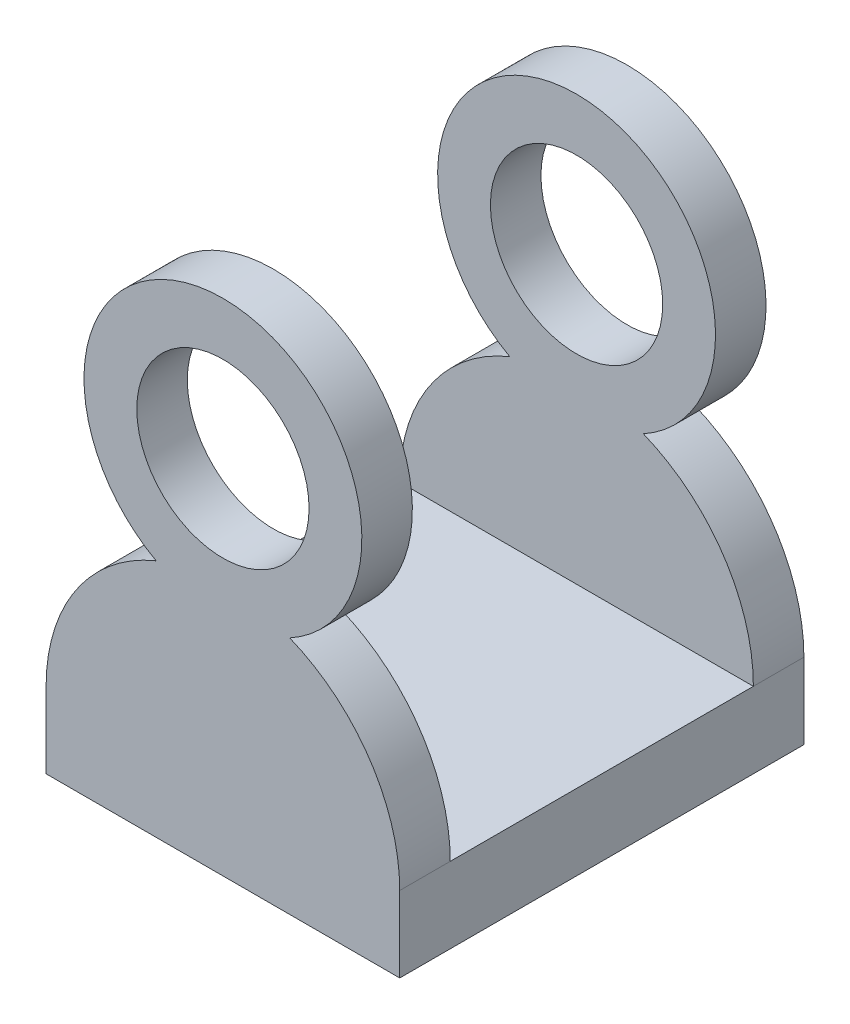
SolidWorks part; units mm, degrees
ref_plane "Front Plane" through (0, 0, 0) normal (0, 0, 1) x (1, 0, 0)
ref_plane "Top Plane" through (0, 0, 0) normal (0, 1, 0) x (1, 0, 0)
ref_plane "Right Plane" through (0, 0, 0) normal (1, 0, 0) x (0, 0, -1)
sketch "Sketch1" plane through (0, 0, 0) normal (0, 0, 1) x (1, 0, 0)
  line L1 (-7, -1.5) -> (7, -1.5)
  line L2 (-7, -1.5) -> (-7, 1.5)
  line L3 (-7, 1.5) -> (7, 1.5)
  line L4 (7, -1.5) -> (7, 1.5)
  line L5 (-7, -1.5) -> (7, 1.5) construction
  line L6 (-7, 1.5) -> (7, -1.5) construction
  point P0 (0, 0)
  dimension "D1" = 3
  dimension "D2" = 14
extrude "Boss-Extrude1" add sketch "Sketch1" along normal blind 16
sketch "Sketch2" plane through (0, 0, 16) normal (0, 0, 1) x (1, 0, 0)
  line L1 (7, 1.5) -> (-7, 1.5) construction
  line L2 (-7, 1.5) -> (7, 1.5)
  arc A0 (7, 1.5) -> (2.6439, 7.9815) centre (0, 1.5) ccw
  arc A1 (2.6439, 7.9815) -> (-2.6439, 7.9815) centre (0, 12.8043) ccw
  arc A2 (-2.6439, 7.9815) -> (-7, 1.5) centre (0, 1.5) ccw
  dimension "D1" = 5.5
extrude "Boss-Extrude2" add sketch "Sketch2" against normal blind 2
sketch "Sketch3" plane through (0, 0, 16) normal (0, 0, 1) x (1, 0, 0)
  line L0 (-7, -1.5) -> (7, -1.5) construction
  circle A0 centre (0, 12.8043) radius 3.41
  point P5 (0, -1.5)
  dimension "D2" = 6.82
extrude "Cut-Extrude2" cut sketch "Sketch3" against normal blind 7.8
ref_plane "Plane2" through (0, 0, 8) normal (0, 0, -1) x (-1, 0, 0)
mirror "Mirror1" about plane through (0, 0, 8) normal (0, 0, -1) of "Cut-Extrude2", "Boss-Extrude2"
sketch "Sketch4" plane through (0, 1.5, 0) normal (0, 1, 0) x (1, 0, 0)
  line L0 (-7, -8) -> (7, -8) construction
  line L1 (-7, -14) -> (-7, -2) construction
  line L2 (7, -14) -> (7, -2) construction
sketch "Sketch5" plane through (0, -1.5, 0) normal (0, -1, 0) x (1, 0, 0)
  line L0 (-7, 8) -> (7, 8) construction
sketch "Sketch6" plane through (0, -1.5, 0) normal (0, -1, 0) x (-1, 0, 0)
  line L0 (0, 0) -> (0, -16) construction
  line L1 (7, -16) -> (-7, -16) construction
